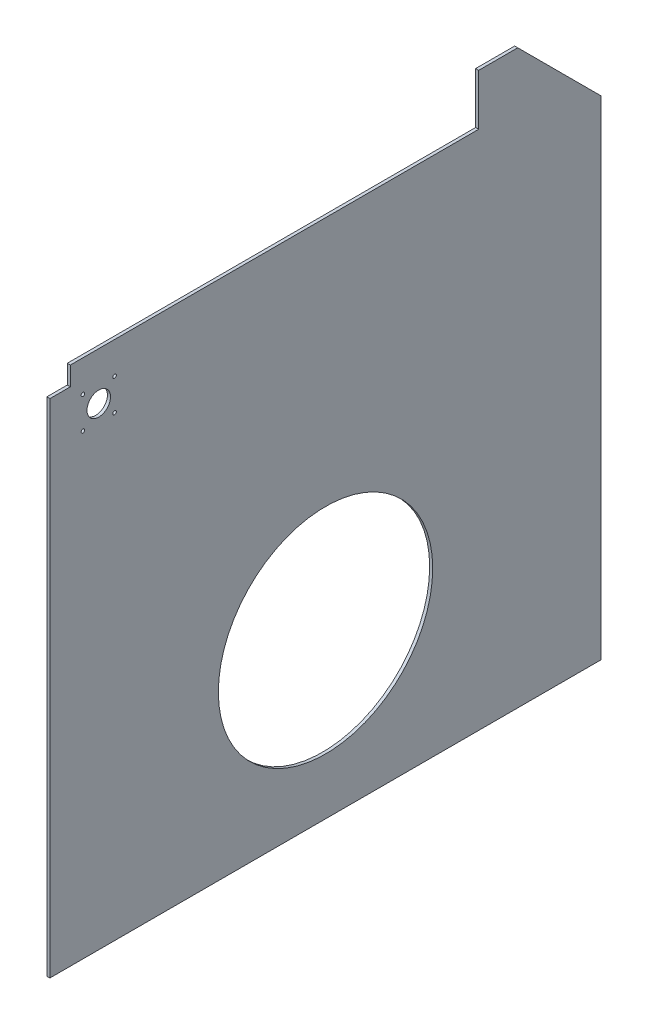
SolidWorks part; units mm, degrees
ref_plane "Front Plane" through (0, 0, 0) normal (0, 0, 1) x (1, 0, 0)
ref_plane "Top Plane" through (0, 0, 0) normal (0, 1, 0) x (1, 0, 0)
ref_plane "Right Plane" through (0, 0, 0) normal (1, 0, 0) x (0, 0, -1)
sketch "Sketch1" plane through (0, 0, 0) normal (1, 0, 0) x (0, 0, -1)
  line L0 (540, 475.6295) -> (540, 478.2843)
  line L1 (0, 0) -> (540, 0)
  line L2 (0, 0) -> (0, 475.6295)
  line L3 (450, 540) -> (20, 540) construction
  line L4 (540, 0) -> (540, 475.6295)
  line L5 (540, 478.2843) -> (458.2843, 560)
  line L6 (458.2843, 560) -> (420, 560)
  line L7 (420, 560) -> (420, 510)
  line L8 (420, 510) -> (20, 510)
  line L9 (20, 491.5197) -> (20, 540) construction
  line L10 (20, 510) -> (20, 491.5197)
  line L11 (20, 491.5197) -> (0, 491.5197)
  line L12 (0, 491.5197) -> (0, 475.6295)
  dimension "D1" = 540
  dimension "D2" = 0
  dimension "D3" = 0
  dimension "D4" = 30
  dimension "D5" = 30
extrude "Boss-Extrude1" add sketch "Sketch1" along normal blind 3
sketch "Sketch3" plane through (0, 0, 0) normal (-1, 0, 0) x (0, 0, 1)
  line L0 (-540, 160) -> (0, 160) construction
  line L1 (-540, 0) -> (-540, 478.2843) construction
  line L2 (0, 491.5197) -> (0, 0) construction
  line L3 (0, 0) -> (-540, 0) construction
  circle A0 centre (-270, 160) radius 105
  dimension "D1" = 210
  dimension "D2" = 160
extrude "Cut-Extrude1" cut sketch "Sketch3" against normal blind 3
sketch "Sketch4" plane through (3, 0, 0) normal (1, 0, 0) x (0, 0, -1)
  line L0 (63.3676, 478.887) -> (32.3676, 478.887) construction
  line L1 (32.3676, 478.887) -> (32.3676, 447.887) construction
  line L2 (32.3676, 447.887) -> (63.3676, 447.887) construction
  line L3 (63.3676, 447.887) -> (32.3676, 478.887) construction
  circle A1 centre (32.3676, 478.887) radius 1.75
  circle A2 centre (32.3676, 447.887) radius 1.75
  circle A3 centre (63.3676, 447.887) radius 1.75
  circle A4 centre (63.3676, 478.887) radius 1.75
  circle A5 centre (47.8676, 463.387) radius 11.5
  point P0 (47.8676, 463.387)
  dimension "D1" = 31
  dimension "D2" = 23
extrude "Cut-Extrude2" cut sketch "Sketch4" against normal blind 15
